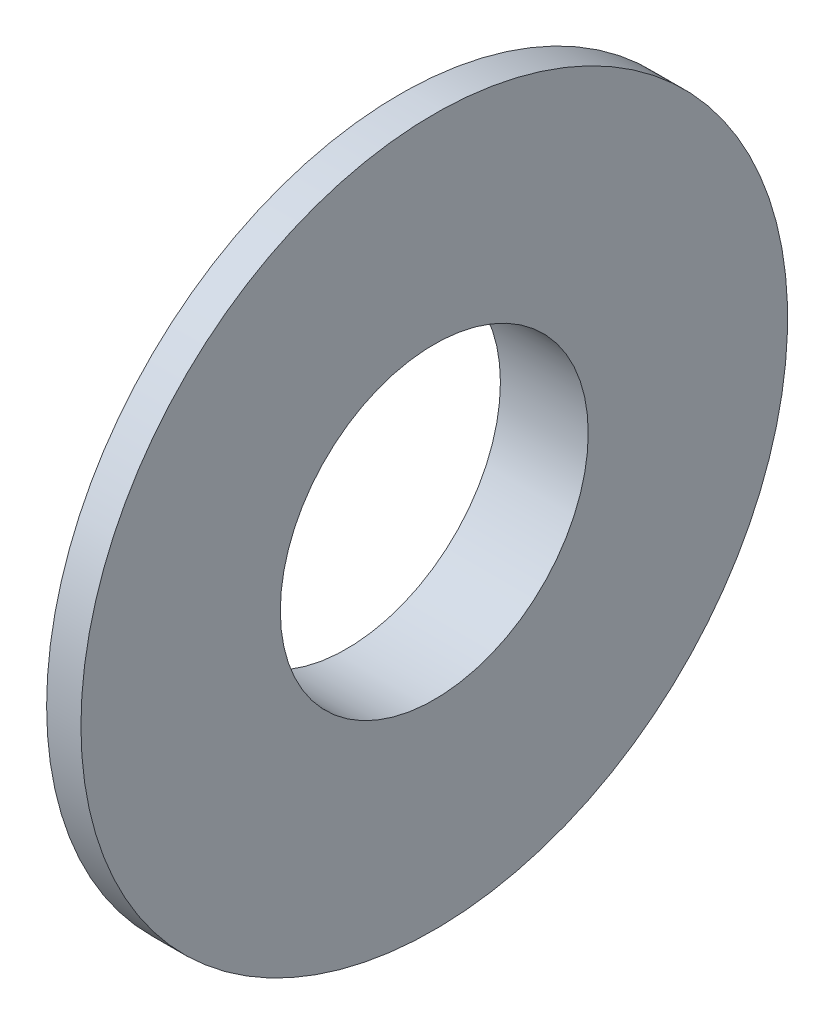
SolidWorks part; units mm, degrees
ref_plane "Front Plane" through (0, 0, 0) normal (0, 0, 1) x (1, 0, 0)
ref_plane "Top Plane" through (0, 0, 0) normal (0, 1, 0) x (1, 0, 0)
ref_plane "Right Plane" through (0, 0, 0) normal (1, 0, 0) x (0, 0, -1)
sketch "Sketch1" plane through (0, 0, 0) normal (0, 0, 1) x (1, 0, 0)
  line L0 (-66.0935, 0) -> (68.7664, 0) construction
  line L1 (0, 13.5) -> (0, 20.0453)
  line L3 (7.7, 30.9813) -> (7.7, 13.5)
  line L4 (7.7, 13.5) -> (0, 13.5)
  line L5 (4.6911, 29.4658) -> (4.6911, 30.9813)
  line L6 (4.6911, 30.9813) -> (7.7, 30.9813)
  line L7 (0, 20.0453) -> (1.0316, 20.0453)
  arc A1 (1.0316, 20.0453) -> (4.6911, 29.4658) centre (13.3786, 20.67) cw
  dimension "D1" = 13.5
  dimension "D2" = 7.7
revolve "Revolve1" add sketch "Sketch1" angle 360 about L0
